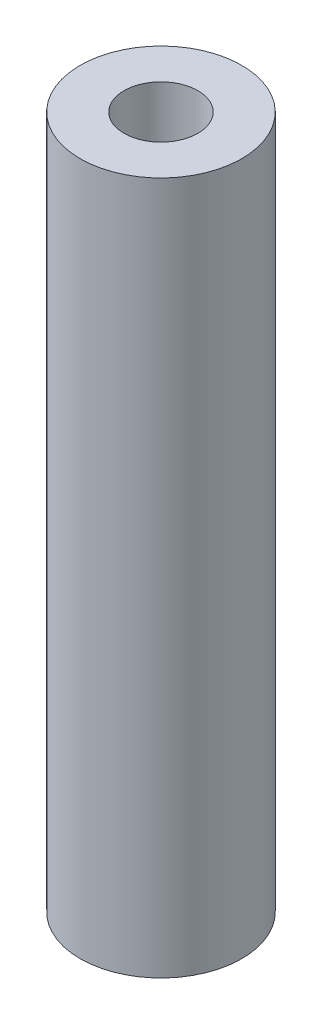
SolidWorks part; units mm, degrees
ref_plane "Front Plane" through (0, 0, 0) normal (0, 0, 1) x (1, 0, 0)
ref_plane "Top Plane" through (0, 0, 0) normal (0, 1, 0) x (1, 0, 0)
ref_plane "Right Plane" through (0, 0, 0) normal (1, 0, 0) x (0, 0, -1)
sketch "Sketch1" plane through (0, 0, 0) normal (0, 1, 0) x (1, 0, 0)
  circle A0 centre (0, 0) radius 1.6
  circle A1 centre (0, 0) radius 3.5
  dimension "D1" = 7
  dimension "3.2" = 3.2
extrude "Boss-Extrude1" add sketch "Sketch1" along normal blind 30
